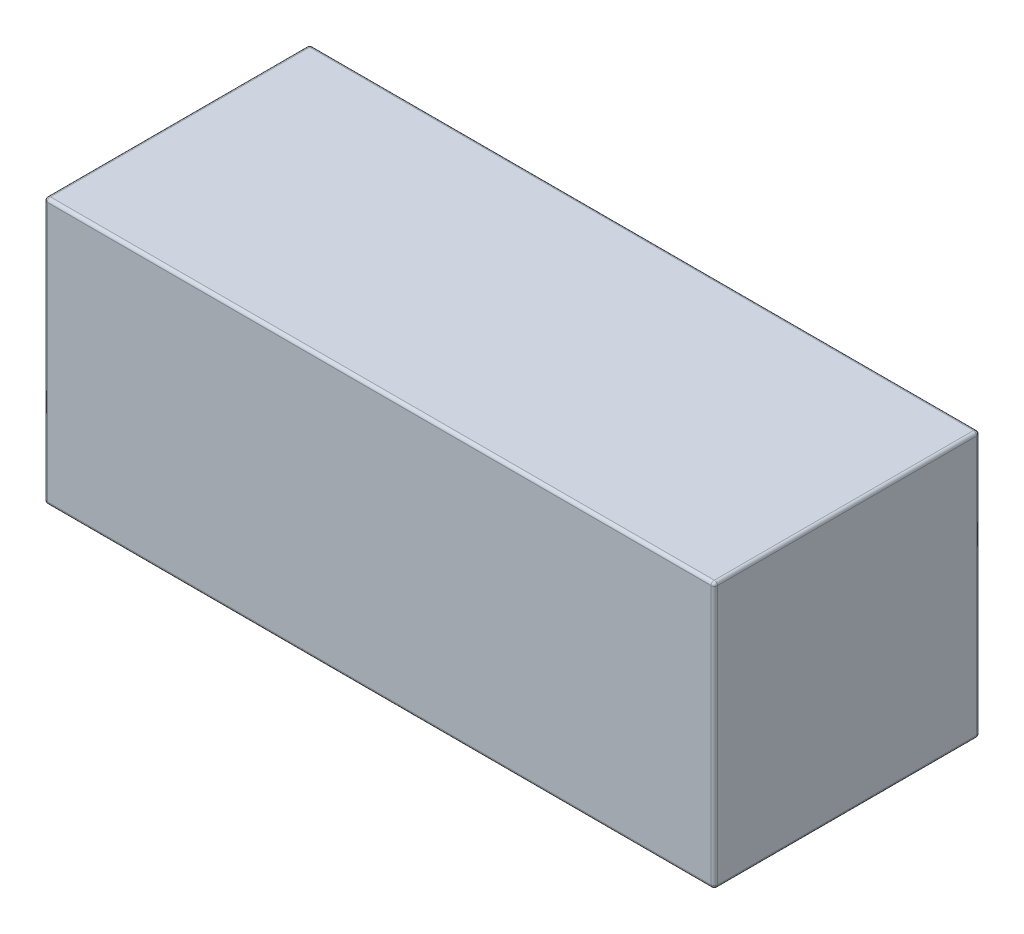
SolidWorks part; units mm, degrees
ref_plane "Plan de face" through (0, 0, 0) normal (0, 0, 1) x (1, 0, 0)
ref_plane "Plan de dessus" through (0, 0, 0) normal (0, 1, 0) x (1, 0, 0)
ref_plane "Plan de droite" through (0, 0, 0) normal (1, 0, 0) x (0, 0, -1)
sketch "Esquisse1" plane through (0, 0, 0) normal (0, 0, 1) x (1, 0, 0)
  line L1 (0, 0) -> (106, 0)
  line L2 (0, 0) -> (0, -42)
  line L3 (0, -42) -> (106, -42)
  line L4 (106, 0) -> (106, -42)
  dimension "D1" = 106
  dimension "D2" = 42
extrude "Boss.-Extru.1" add sketch "Esquisse1" along normal blind 42
sketch "Esquisse2" plane through (0, -42, 0) normal (0, -1, 0) x (1, 0, 0)
  line L1 (59.75, 38.25) -> (70.25, 38.25)
  line L2 (59.75, 38.25) -> (59.75, 27.75)
  line L3 (59.75, 27.75) -> (70.25, 27.75)
  line L4 (70.25, 38.25) -> (70.25, 27.75)
  line L5 (88.75, 3.75) -> (99.25, 3.75)
  line L6 (0, 0) -> (106, 0) construction
  line L7 (106, 42) -> (106, 0) construction
  line L8 (88.75, 3.75) -> (88.75, 14.25)
  line L9 (88.75, 14.25) -> (99.25, 14.25)
  line L10 (0, 42) -> (106, 42) construction
  line L11 (99.25, 3.75) -> (99.25, 14.25)
  line L12 (88.75, 27.75) -> (99.25, 27.75)
  line L13 (59.75, 14.25) -> (70.25, 14.25)
  line L14 (59.75, 14.25) -> (59.75, 3.75)
  line L15 (59.75, 3.75) -> (70.25, 3.75)
  line L16 (70.25, 14.25) -> (70.25, 3.75)
  line L17 (88.75, 27.75) -> (88.75, 38.25)
  line L18 (88.75, 38.25) -> (99.25, 38.25)
  line L19 (99.25, 27.75) -> (99.25, 38.25)
  point P4 (70.25, 9)
  point P7 (106, 21)
  point P10 (53, 42)
  point P11 (65, 38.25)
  point P16 (65, 3.75)
  point P20 (53, 0)
  point P21 (70.25, 33)
  point P29 (94, 27.75)
  point P30 (94, 14.25)
  point P31 (94, 38.25)
  dimension "D1" = 10.5
  dimension "D2" = 10.5
  dimension "D3" = 10.5
  dimension "D4" = 10.5
  dimension "D5" = 12
  dimension "D6" = 12
  dimension "D7" = 12
  dimension "D8" = 12
  dimension "D9" = 10.5
  dimension "D10" = 10.5
  dimension "D11" = 29
  dimension "D12" = 29
extrude "Enlèv. mat.-Extru.1" cut sketch "Esquisse2" against normal blind 4.5
ref_plane "Plan1" through (0, 0, 21) normal (0, 0, 1) x (1, 0, 0)
ref_plane "Plan2" through (53, 0, 0) normal (1, 0, 0) x (0, 0, -1)
ref_plane "Plan3" through (37, 0, 37) normal (0.7071, 0, 0.7071) x (0.7071, 0, -0.7071)
fillet "Congé1" radius 0.5 12 edges at (0, -42, 21) (53, -42, 42) (0, -21, 42) (106, -42, 21) (106, -21, 42) (53, -42, 0) (106, -21, 0) (0, -21, 0) (106, 0, 21) (53, 0, 42) (0, 0, 21) (53, 0, 0)
mirror "Symétrie1" about plane through (53, 0, 0) normal (1, 0, 0) of "Enlèv. mat.-Extru.1"
ref_plane "Plan4" through (35.75, -42, 14.25) normal (1, 0, 0) x (0, 0, -1)
chamfer "Chanfrein1" distance 0.5 angle 45 32 edges at (94, -42, 38.25) (88.75, -42, 33) (94, -42, 27.75) (99.25, -42, 33) (94, -42, 14.25) (88.75, -42, 9) (94, -42, 3.75) (99.25, -42, 9) (59.75, -42, 9) (65, -42, 14.25) (65, -42, 3.75) (70.25, -42, 9) (41, -42, 14.25) (35.75, -42, 9) (41, -42, 3.75) (46.25, -42, 9) (70.25, -42, 33) (65, -42, 27.75) (59.75, -42, 33) (65, -42, 38.25) (41, -42, 27.75) (46.25, -42, 33) (35.75, -42, 33) (41, -42, 38.25) (17.25, -42, 33) (12, -42, 27.75) (6.75, -42, 33) (12, -42, 38.25) (17.25, -42, 9) (12, -42, 3.75) (6.75, -42, 9) (12, -42, 14.25)
